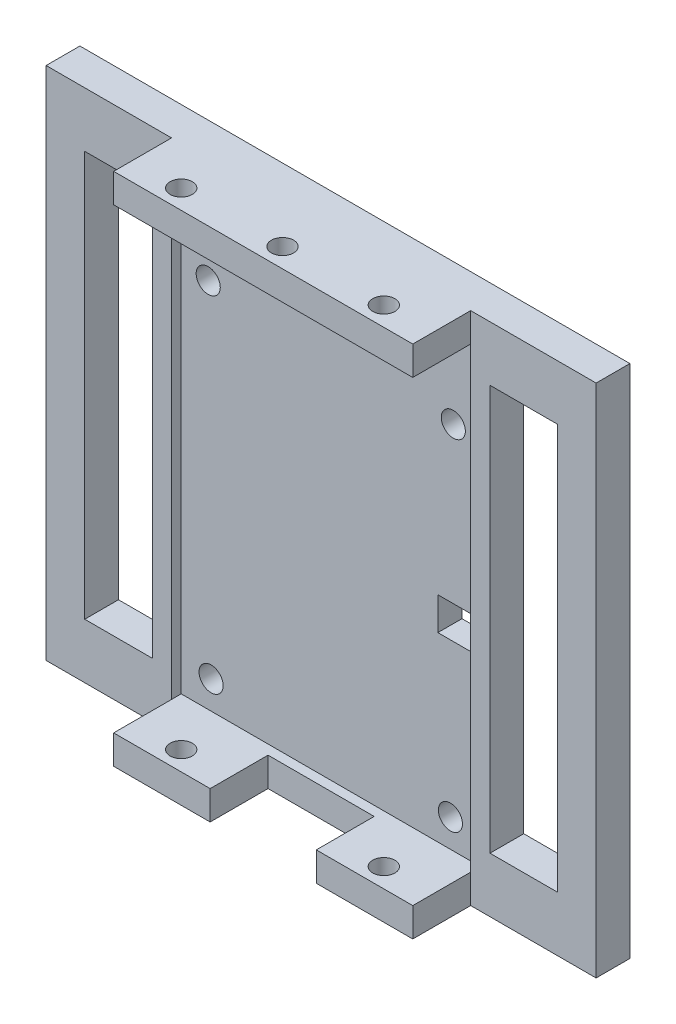
SolidWorks part; units mm, degrees
ref_plane "前视基准面" through (0, 0, 0) normal (0, 0, 1) x (1, 0, 0)
ref_plane "上视基准面" through (0, 0, 0) normal (0, 1, 0) x (1, 0, 0)
ref_plane "右视基准面" through (0, 0, 0) normal (1, 0, 0) x (0, 0, -1)
sketch "草图1" plane through (0, 0, 0) normal (0, 0, 1) x (1, 0, 0)
  line L0 (-15, 21) -> (16, 21)
  line L1 (-15, 27) -> (16, 27)
  line L2 (-15, 27) -> (-15, -20)
  line L3 (-15, -20) -> (16, -20)
  line L4 (16, 27) -> (16, -20)
  line L5 (-17, 29) -> (-28, 29)
  line L6 (-17, 29) -> (18, 29)
  line L7 (-17, 29) -> (-17, -22)
  line L8 (-17, -22) -> (18, -22)
  line L9 (18, 29) -> (18, -22)
  line L10 (-28, 29) -> (-28, -22)
  line L11 (-28, -22) -> (-17, -22)
  line L12 (18, 29) -> (29, 29)
  line L13 (29, 29) -> (29, -22)
  line L14 (29, -22) -> (18, -22)
  line L15 (-17, 24.5) -> (-24, 24.5)
  line L16 (-24, 24.5) -> (-24, -17.5)
  line L17 (-24, -17.5) -> (-17, -17.5)
  line L18 (18, 24.5) -> (25, 24.5)
  line L19 (25, 24.5) -> (25, -17.5)
  line L20 (25, -17.5) -> (18, -17.5)
  line L22 (11.6, 2) -> (15, 2)
  line L23 (11.6, 2) -> (11.6, -1.4)
  line L24 (11.6, -1.4) -> (15, -1.4)
  line L25 (15, 2) -> (15, -1.4)
  dimension "D1" = 47
  dimension "D2" = 31
  dimension "D3" = 41
  dimension "D4" = 20
  dimension "D5" = 15
  dimension "D6" = 2
  dimension "D7" = 2
  dimension "D8" = 2
  dimension "D9" = 2
  dimension "D10" = 42
  dimension "D11" = 42
  dimension "D12" = 4.5
  dimension "D13" = 4
  dimension "D14" = 4
  dimension "D15" = 7
  dimension "D16" = 7
  dimension "D17" = 19
  dimension "D18" = 3.4
  dimension "D19" = 3.4
  dimension "D20" = 1
extrude "凸台-拉伸1" add sketch "草图1" along normal blind 3 contours L17 L16 L15 L7 L5 L10 L11 | L9 L6 L7 L8 L1 L4 L3 L2 | L4 L1 L2 L0 | L4 L0 L2 L3 | L19 L20 L9 L14 L13 L12 L18
sketch "草图2" plane through (0, 0, 3) normal (0, 0, 1) x (1, 0, 0)
  line L0 (-15, 27) -> (-15, -20)
  line L1 (-15, -20) -> (16, -20)
  line L2 (16, -20) -> (16, 27)
  line L3 (16, 27) -> (-15, 27)
extrude "切除-拉伸1" cut sketch "草图2" against normal blind 1
sketch "草图3" plane through (0, 0, 2) normal (0, 0, 1) x (1, 0, 0)
  line L0 (-15, 27) -> (-15, -20) construction
  line L1 (-15, 21) -> (16, 21) construction
  line L2 (16, -20) -> (16, 27) construction
  line L3 (-15, 27) -> (-15, -20) construction
  line L4 (-15, -20) -> (16, -20) construction
  circle A0 centre (-12.2, 18.3) radius 1.25
  circle A1 centre (13.2, 18.1) radius 1.25
  circle A2 centre (12.9, -17.3) radius 1.25
  circle A3 centre (-11.9, -17.3) radius 1.25
  dimension "D3" = 2.5
  dimension "D5" = 2.8
  dimension "D6" = 2.5
  dimension "D7" = 2.5
  dimension "D9" = 2.7
  dimension "D10" = 3.1
  dimension "D11" = 2.5
  dimension "D12" = 2.7
  dimension "D1" = 2.8
  dimension "D2" = 2.7
  dimension "D4" = 2.9
  dimension "D8" = 3.1
extrude "切除-拉伸2" cut sketch "草图3" against normal through all
sketch "草图5" plane through (0, 29, 0) normal (0, 1, 0) x (1, 0, 0)
  line L0 (-28, 0) -> (-28, -3)
  line L1 (-28, -3) -> (29, -3)
  line L2 (29, -3) -> (29, 0)
  line L3 (29, 0) -> (-28, 0)
extrude "凸台-拉伸2" add sketch "草图5" along normal blind 1
sketch "草图6" plane through (0, -22, 0) normal (0, -1, 0) x (-1, 0, 0)
  line L0 (28, -3) -> (28, 0)
  line L1 (28, 0) -> (-29, 0)
  line L2 (-29, 0) -> (-29, -3)
  line L3 (-29, -3) -> (28, -3)
extrude "凸台-拉伸3" add sketch "草图6" along normal blind 1
sketch "草图7" plane through (0, 0, 3) normal (0, 0, 1) x (1, 0, 0)
  line L0 (-15, -20) -> (-15, -23)
  line L1 (29, -23) -> (-28, -23) construction
  line L2 (-15, -23) -> (-5, -23)
  line L3 (-5, -23) -> (-5, -20)
  line L4 (-15, -20) -> (16, -20) construction
  line L5 (-5, -20) -> (-15, -20)
  line L6 (16, -20) -> (16, -23)
  line L7 (16, -23) -> (6, -23)
  line L8 (6, -23) -> (6, -20)
  line L9 (6, -20) -> (16, -20)
  dimension "D1" = 10
  dimension "D2" = 10
extrude "凸台-拉伸4" add sketch "草图7" along normal blind 6
sketch "草图8" plane through (0, 0, 3) normal (0, 0, 1) x (1, 0, 0)
  line L0 (-15, 27) -> (-15, 30)
  line L1 (-28, 30) -> (29, 30) construction
  line L2 (-15, 30) -> (16, 30)
  line L3 (16, 30) -> (16, 27)
  line L4 (16, 27) -> (-15, 27)
extrude "凸台-拉伸5" add sketch "草图8" along normal blind 6
sketch "草图9" plane through (0, -23, 0) normal (0, -1, 0) x (1, 0, 0)
  line L0 (-15, 9) -> (-15, 3) construction
  line L2 (-15, 9) -> (-5, 9) construction
  line L4 (6, 9) -> (6, 3) construction
  line L5 (6, 9) -> (16, 9) construction
  circle A0 centre (-10, 7) radius 1.15
  circle A1 centre (11, 7) radius 1.15
  dimension "D3" = 2.3
  dimension "D6" = 2.3
  dimension "D1" = 5
  dimension "D2" = 2
  dimension "D4" = 5
  dimension "D5" = 2
extrude "切除-拉伸3" cut sketch "草图9" against normal up to next
sketch "草图10" plane through (0, 30, 0) normal (0, 1, 0) x (1, 0, 0)
  line L0 (16, -9) -> (16, -3) construction
  line L1 (16, -9) -> (-15, -9) construction
  line L2 (-15, -9) -> (-15, -3) construction
  circle A0 centre (-10, -7) radius 1.15
  circle A1 centre (0.5, -7) radius 1.15
  circle A2 centre (11, -7) radius 1.15
  dimension "D1" = 2.3
  dimension "D2" = 2.3
  dimension "D3" = 2.3
  dimension "D4" = 5
  dimension "D5" = 2
  dimension "D6" = 2
  dimension "D7" = 2
  dimension "D8" = 5
  dimension "D9" = 10.5
extrude "切除-拉伸4" cut sketch "草图10" against normal up to next
sketch "草图12" plane through (0, 0, 0) normal (0, 0, -1) x (-1, 0, 0)
  line L0 (-29, 30) -> (-29, -23)
  line L1 (-29, -23) -> (28, -23)
  line L2 (28, -23) -> (28, 30)
  line L3 (28, 30) -> (-29, 30)
  circle M1 centre (11.9, -17.3) radius 1.25
  circle M2 centre (-12.9, -17.3) radius 1.25
  circle M3 centre (-13.2, 18.1) radius 1.25
  circle M4 centre (12.2, 18.3) radius 1.25
  line M5 (-18, 24.5) -> (-18, -17.5)
  line M6 (-18, -17.5) -> (-25, -17.5)
  line M7 (-25, -17.5) -> (-25, 24.5)
  line M8 (-25, 24.5) -> (-18, 24.5)
  line M9 (17, 24.5) -> (24, 24.5)
  line M10 (24, 24.5) -> (24, -17.5)
  line M11 (24, -17.5) -> (17, -17.5)
  line M12 (17, -17.5) -> (17, 24.5)
  line M13 (-29, 30) -> (-29, -23)
  line M14 (-29, -23) -> (28, -23)
  line M15 (28, -23) -> (28, 30)
  line M16 (28, 30) -> (-29, 30)
  line M17 (-15, 2) -> (-11.6, 2)
  line M18 (-11.6, 2) -> (-11.6, -1.4)
  line M19 (-11.6, -1.4) -> (-15, -1.4)
  line M20 (-15, -1.4) -> (-15, 2)
extrude "凸台-拉伸6" add sketch "草图12" along normal blind 0.5 contours M16 M13 M14 M15 M2 M4 M20 M17 M18 M19 M12 M9 M10 M11 M8 M5 M6 M7 M3 M1
sketch "草图13" plane through (0, 30, 0) normal (0, 1, 0) x (1, 0, 0)
  line L1 (-29.9909, 3.5633) -> (33.3625, 3.5633)
  line L2 (-29.9909, 3.5633) -> (-29.9909, -10.0729)
  line L3 (-29.9909, -10.0729) -> (33.3625, -10.0729)
  line L4 (33.3625, 3.5633) -> (33.3625, -10.0729)
  circle M1 centre (-10, -7) radius 1.15
  circle M2 centre (0.5, -7) radius 1.15
  circle M3 centre (11, -7) radius 1.15
  line M4 (29, -3) -> (29, 0.5)
  line M5 (29, 0.5) -> (-28, 0.5)
  line M6 (-28, 0.5) -> (-28, -3)
  line M7 (-28, -3) -> (-15, -3)
  line M8 (-15, -3) -> (-15, -9)
  line M9 (-15, -9) -> (16, -9)
  line M10 (16, -9) -> (16, -3)
  line M11 (16, -3) -> (29, -3)
extrude "凸台-拉伸7" add sketch "草图13" along normal blind 0.2 contours M11 M4 M5 M6 M7 M8 M9 M10 M2 M3 M1
sketch "草图14" plane through (0, -23, 0) normal (0, -1, 0) x (-1, 0, 0)
  line L1 (30.8379, -11.301) -> (-34.2094, -11.301)
  line L2 (30.8379, -11.301) -> (30.8379, 3.2245)
  line L3 (30.8379, 3.2245) -> (-34.2094, 3.2245)
  line L4 (-34.2094, -11.301) -> (-34.2094, 3.2245)
  circle M1 centre (10, -7) radius 1.15
  circle M2 centre (-11, -7) radius 1.15
  line M3 (-29, -3) -> (-16, -3)
  line M4 (-16, -3) -> (-16, -9)
  line M5 (-16, -9) -> (-6, -9)
  line M6 (-6, -9) -> (-6, -3)
  line M7 (-6, -3) -> (5, -3)
  line M8 (5, -3) -> (5, -9)
  line M9 (5, -9) -> (15, -9)
  line M10 (15, -9) -> (15, -3)
  line M11 (15, -3) -> (28, -3)
  line M12 (28, -3) -> (28, 0.5)
  line M13 (28, 0.5) -> (-29, 0.5)
  line M14 (-29, 0.5) -> (-29, -3)
extrude "凸台-拉伸8" add sketch "草图14" along normal blind 0.2 contours M14 M3 M4 M5 M6 M7 M8 M9 M10 M11 M12 M13 M2 M1
sketch "草图15" plane through (0, -20, 0) normal (0, 1, 0) x (1, 0, 0)
  line L1 (-18.0823, -0.9428) -> (19.793, -0.9428)
  line L2 (-18.0823, -0.9428) -> (-18.0823, -10.4425)
  line L3 (-18.0823, -10.4425) -> (19.793, -10.4425)
  line L4 (19.793, -0.9428) -> (19.793, -10.4425)
  circle M5 centre (-10, -7) radius 1.15
  circle M6 centre (11, -7) radius 1.15
  line M7 (-15, -2) -> (-15, -3)
  line M8 (-15, -3) -> (-15, -9)
  line M9 (-15, -9) -> (-5, -9)
  line M10 (-5, -9) -> (-5, -3)
  line M11 (-5, -3) -> (6, -3)
  line M12 (6, -3) -> (6, -9)
  line M13 (6, -9) -> (16, -9)
  line M14 (16, -9) -> (16, -3)
  line M15 (16, -3) -> (16, -2)
  line M16 (16, -2) -> (-15, -2)
extrude "切除-拉伸5" cut sketch "草图15" against normal blind 0.2 contours M16 M7 M8 M9 M10 M11 M12 M13 M14 M15 M6 M5
sketch "草图16" plane through (0, 27, 0) normal (0, -1, 0) x (1, 0, 0)
  line L1 (-17.117, 10.8775) -> (19.0487, 10.8775)
  line L2 (-17.117, 10.8775) -> (-17.117, 0.5869)
  line L3 (-17.117, 0.5869) -> (19.0487, 0.5869)
  line L4 (19.0487, 10.8775) -> (19.0487, 0.5869)
  circle M5 centre (-10, 7) radius 1.15
  circle M6 centre (0.5, 7) radius 1.15
  circle M7 centre (11, 7) radius 1.15
  line M8 (16, 2) -> (16, 3)
  line M9 (16, 3) -> (16, 9)
  line M10 (16, 9) -> (-15, 9)
  line M11 (-15, 9) -> (-15, 3)
  line M12 (-15, 3) -> (-15, 2)
  line M13 (-15, 2) -> (16, 2)
extrude "切除-拉伸6" cut sketch "草图16" against normal blind 0.2 contours M13 M8 M9 M10 M11 M12 M6 M7 M5
